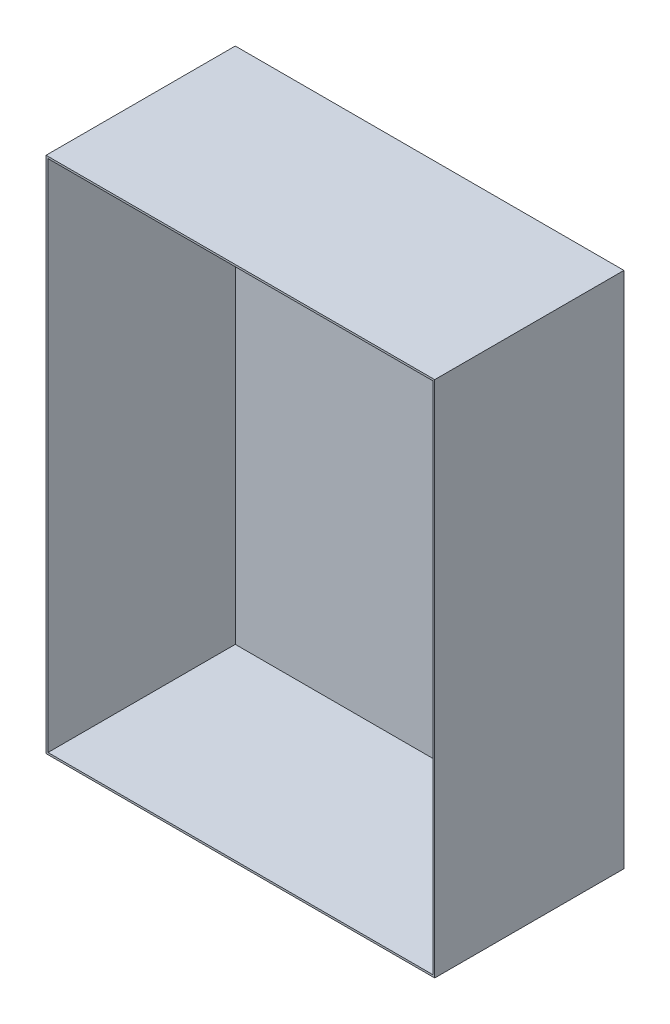
SolidWorks part; units mm, degrees
ref_plane "Front Plane" through (0, 0, 0) normal (0, 0, 1) x (1, 0, 0)
ref_plane "Top Plane" through (0, 0, 0) normal (0, 1, 0) x (1, 0, 0)
ref_plane "Right Plane" through (0, 0, 0) normal (1, 0, 0) x (0, 0, -1)
sketch "Sketch1" plane through (0, 0, 0) normal (0, 0, 1) x (1, 0, 0)
  line L1 (-150, -200) -> (150, -200)
  line L2 (-150, -200) -> (-150, 200)
  line L3 (-150, 200) -> (150, 200)
  line L4 (150, -200) -> (150, 200)
  line L5 (-150, -200) -> (150, 200) construction
  line L6 (-150, 200) -> (150, -200) construction
  point P0 (0, 0)
  dimension "D1" = 400
  dimension "D2" = 300
extrude "Boss-Extrude1" add sketch "Sketch1" along normal blind 146.05
shell "Shell1" thickness 1.5
sketch "Solenoid Port Cutouts"
  dimension "D4" = 19.05
  dimension "D5" = 5.25
  dimension "D1" = 245
  dimension "D2" = 90
  dimension "D3" = 28.025
  dimension "D6" = 8.5
  dimension "D7" = 50
  dimension "D8" = 50
  dimension "D9" = 27.4997
  dimension "D10" = 8.5
  dimension "D11" = 8.5
  dimension "D13" = 19.2
  dimension "D14" = 12.15
  dimension "D12" = 14
sketch_block_instance "XT60E-F-1"
sketch_block "XT60E-F"
sketch "Sketch3" plane through (150, 0, 0) normal (1, 0, 0) x (0, 0, -1)
  line L0 (-146.05, 200) -> (0, 200) construction
  line L1 (-120.5532, 161.1593) -> (-25.4968, 161.1593) construction
  line L2 (-120.5532, 161.1593) -> (-120.5532, -161.1585) construction
  line L3 (-120.5532, -161.1585) -> (-25.4968, -161.1585) construction
  line L4 (-25.4968, 161.1593) -> (-25.4968, -161.1585) construction
  line L5 (0, -200) -> (0, 200) construction
  dimension "D1" = 95.0565
  dimension "D2" = 322.3179
  dimension "D3" = 38.8407
  dimension "D4" = 25.4968
equation "\"D3@Solenoid Port Cutouts\" =  ( 5.75 - \"D2@Solenoid Port Cutouts\" )  / 2"
equation "\"D8@Solenoid Port Cutouts\" = \"D7@Solenoid Port Cutouts\""
equation "\"D9@Solenoid Port Cutouts\" =  ( 11.811 - \"D1@Solenoid Port Cutouts\" )  / 2"
equation "\"D10@Solenoid Port Cutouts\" = \"D6@Solenoid Port Cutouts\""
equation "\"D11@Solenoid Port Cutouts\" = \"D6@Solenoid Port Cutouts\""
equation "\"D3@Sketch3\"=(15.748-\"D2@Sketch3\")/2"
equation "\"D4@Sketch3\"=(5.75-\"D1@Sketch3\")/2"
equation "\"D7@XT60E-F\"=\"D5@XT60E-F\"/2"
equation "\"D8@XT60E-F\"=\"D6@XT60E-F\"/2"
